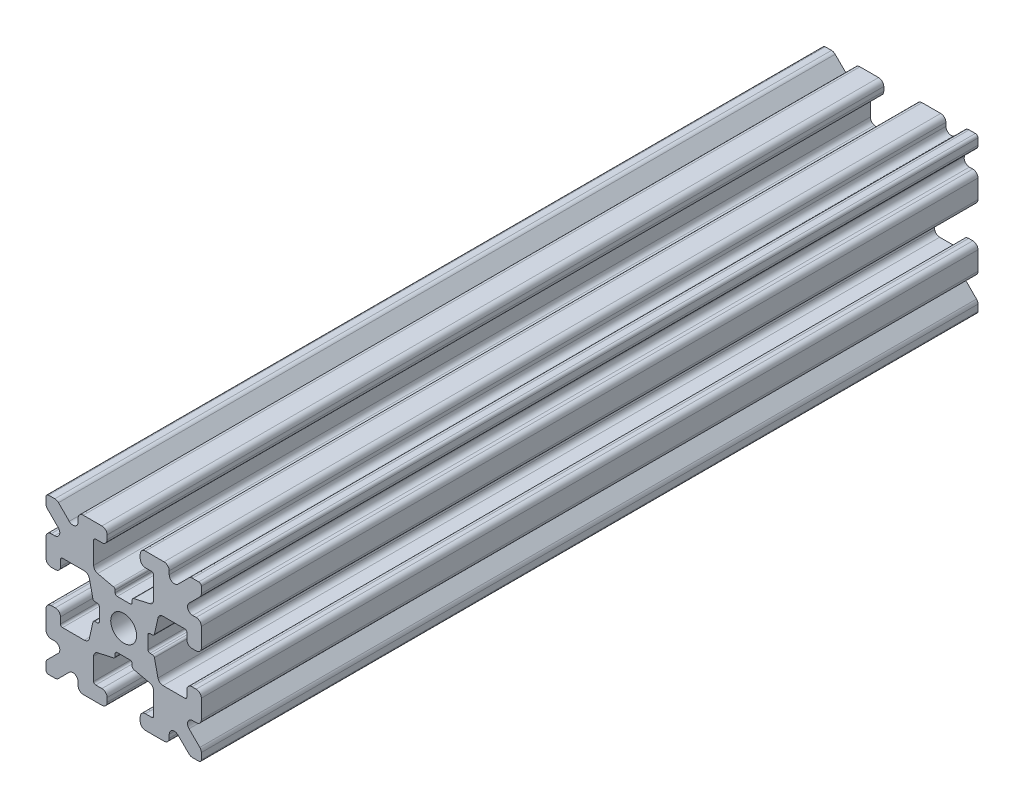
SolidWorks part; units mm, degrees
ref_plane "Front Plane" through (0, 0, 0) normal (0, 0, 1) x (1, 0, 0)
ref_plane "Top Plane" through (0, 0, 0) normal (0, 1, 0) x (1, 0, 0)
ref_plane "Right Plane" through (0, 0, 0) normal (1, 0, 0) x (0, 0, -1)
sketch "Sketch1" plane through (0, 0, 0) normal (0, 0, 1) x (1, 0, 0)
  line L1 (-7.5, -7.5) -> (7.5, -7.5)
  line L2 (-7.5, -7.5) -> (-7.5, 7.5)
  line L3 (-7.5, 7.5) -> (7.5, 7.5)
  line L4 (7.5, -7.5) -> (7.5, 7.5)
  line L5 (-7.5, -7.5) -> (7.5, 7.5) construction
  line L6 (-7.5, 7.5) -> (7.5, -7.5) construction
  circle A0 centre (0, 0) radius 1.25
  point P0 (0, 0)
  dimension "D2" = 2.5
  dimension "D1" = 15
extrude "Boss-Extrude1" add sketch "Sketch1" along normal mid plane 75
fillet "Fillet1" radius 0.25 4 edges at (7.5, -7.5, 0) (-7.5, -7.5, 0) (7.5, 7.5, 0) (-7.5, 7.5, 0)
sketch "Sketch2" plane through (0, 0, 37.5) normal (0, 0, 1) x (1, 0, 0)
  line L0 (-7.5, 7.25) -> (-7.5, -7.25) construction
  line L1 (-7.5, 1.6) -> (-6.1, 1.6)
  line L2 (-7.5, 1.6) -> (-7.5, -1.6)
  line L3 (-7.5, -1.6) -> (-6.1, -1.6)
  line L4 (-6.1, 1.6) -> (-6.1, 2.9)
  line L5 (0, 0) -> (-12.1036, 0) construction
  line L6 (-6.1, -2.9) -> (-3.4, -2.9)
  line L7 (0, 0) -> (-7.25, 7.25) construction
  line L8 (-6.1, 2.9) -> (-3.4, 2.9)
  line L9 (-3.4, -2.9) -> (-3.4, 2.9)
  line L10 (55, 0) -> (-55, 0) construction
  line L11 (-6.1, -2.9) -> (-6.1, -1.6)
  line L12 (2.9, 6.1) -> (1.6, 6.1)
  line L13 (2.9, 3.4) -> (-2.9, 3.4)
  line L14 (-2.9, 6.1) -> (-2.9, 3.4)
  line L15 (2.9, 6.1) -> (2.9, 3.4)
  line L16 (-1.6, 6.1) -> (-2.9, 6.1)
  line L17 (1.6, 7.5) -> (1.6, 6.1)
  line L18 (-1.6, 7.5) -> (1.6, 7.5)
  line L19 (-1.6, 7.5) -> (-1.6, 6.1)
  line L20 (-1.6, -7.5) -> (-1.6, -6.1)
  line L21 (-1.6, -7.5) -> (1.6, -7.5)
  line L22 (1.6, -7.5) -> (1.6, -6.1)
  line L23 (-1.6, -6.1) -> (-2.9, -6.1)
  line L24 (2.9, -6.1) -> (2.9, -3.4)
  line L25 (-2.9, -6.1) -> (-2.9, -3.4)
  line L26 (2.9, -3.4) -> (-2.9, -3.4)
  line L27 (2.9, -6.1) -> (1.6, -6.1)
  line L28 (6.1, -2.9) -> (6.1, -1.6)
  line L29 (3.4, -2.9) -> (3.4, 2.9)
  line L30 (6.1, 2.9) -> (3.4, 2.9)
  line L31 (6.1, -2.9) -> (3.4, -2.9)
  line L32 (6.1, 1.6) -> (6.1, 2.9)
  line L33 (7.5, -1.6) -> (6.1, -1.6)
  line L34 (7.5, 1.6) -> (7.5, -1.6)
  line L35 (7.5, 1.6) -> (6.1, 1.6)
  dimension "D1" = 3.2
  dimension "D2" = 5.8
  dimension "D3" = 1.4
  dimension "D4" = 2.7
extrude "Cut-Extrude1" cut sketch "Sketch2" against normal through all
sketch "Sketch4" plane through (0, 0, 37.5) normal (0, 0, 1) x (1, 0, 0)
  line L0 (-3.4, 2.9) -> (-2.75, 0)
  line L1 (55, 0) -> (-55, 0) construction
  line L2 (-2.75, 0) -> (-3.4, -2.9)
  line L3 (-3.4, -2.9) -> (-3.4, 2.9) construction
  line L4 (-3.4, 2.9) -> (-3.4, -2.9)
  line L5 (-2.9, 3.4) -> (0, 2.75)
  line L6 (0, 2.75) -> (2.9, 3.4)
  line L7 (2.9, 3.4) -> (-2.9, 3.4)
  line L8 (3.4, 2.9) -> (2.75, 0)
  line L9 (2.75, 0) -> (3.4, -2.9)
  line L10 (3.4, -2.9) -> (3.4, 2.9)
  line L11 (-2.9, -3.4) -> (0, -2.75)
  line L12 (0, -2.75) -> (2.9, -3.4)
  line L13 (2.9, -3.4) -> (-2.9, -3.4)
  circle A2 centre (0, 0) radius 2.75
  circle A3 centre (0, 0) radius 2.75 construction
  dimension "D1" = 1.5
extrude "Cut-Extrude3" cut sketch "Sketch4" against normal through all
fillet "Fillet3" radius 0.5 16 edges at (-6.1, -1.6, 0) (-7.5, -1.6, 0) (-6.1, 1.6, 0) (-7.5, 1.6, 0) (-1.6, -7.5, 0) (-1.6, -6.1, 0) (1.6, -7.5, 0) (1.6, -6.1, 0) (6.1, -1.6, 0) (7.5, -1.6, 0) (7.5, 1.6, 0) (6.1, 1.6, 0) (1.6, 7.5, 0) (1.6, 6.1, 0) (-1.6, 7.5, 0) (-1.6, 6.1, 0)
fillet "Fillet4" radius 0.5 8 edges at (-3.4, 2.9, 0) (-3.4, -2.9, 0) (2.9, -3.4, 0) (-2.9, -3.4, 0) (3.4, -2.9, 0) (3.4, 2.9, 0) (-2.9, 3.4, 0) (2.9, 3.4, 0)
fillet "Fillet5" radius 3 4 edges at (0, -2.75, 0) (2.75, 0, 0) (-2.75, 0, 0) (0, 2.75, 0)
fillet "Fillet6" radius 0.2 8 edges at (-2.9, -6.1, 0) (2.9, -6.1, 0) (6.1, -2.9, 0) (6.1, 2.9, 0) (2.9, 6.1, 0) (-2.9, 6.1, 0) (-6.1, -2.9, 0) (-6.1, 2.9, 0)
sketch "Sketch5" plane through (0, 0, 37.5) normal (0, 0, 1) x (1, 0, 0)
  line L0 (0, 0) -> (-7.25, 7.25) construction
  line L1 (-7.5, 6.4393) -> (-5.4607, 4.4)
  line L2 (-6.4393, 7.5) -> (-4.4, 5.4607)
  line L3 (-7.5, 4.4) -> (-5.4607, 4.4)
  line L4 (-3.8003, 2.9) -> (-5.9, 2.9) construction
  line L5 (0, 0) -> (-12.1819, 0) construction
  line L6 (-4.4, 7.5) -> (-4.4, 5.4607)
  line L7 (-2.9, 5.9) -> (-2.9, 3.8003) construction
  line L8 (-7.5, 6.4393) -> (-7.5, 4.4)
  line L9 (-7.5, 7.25) -> (-7.5, 2.1) construction
  line L10 (2.1, -7.5) -> (7.25, -7.5) construction
  line L11 (7.5, -7.25) -> (7.5, -2.1) construction
  line L12 (7.25, 7.5) -> (2.1, 7.5) construction
  line L13 (-2.1, 7.5) -> (-7.25, 7.5) construction
  line L14 (-4.4, 7.5) -> (-6.4393, 7.5)
  line L16 (55, 0) -> (-55, 0) construction
  line L17 (0, 0) -> (0, 10.993) construction
  line L18 (0, -54.6431) -> (0, 54.6431) construction
  line L20 (4.4, 7.5) -> (6.4393, 7.5)
  line L22 (7.5, 6.4393) -> (7.5, 4.4)
  line L23 (4.4, 7.5) -> (4.4, 5.4607)
  line L24 (7.5, 4.4) -> (5.4607, 4.4)
  line L25 (6.4393, 7.5) -> (4.4, 5.4607)
  line L26 (7.5, 6.4393) -> (5.4607, 4.4)
  line L27 (7.5, -6.4393) -> (5.4607, -4.4)
  line L28 (6.4393, -7.5) -> (4.4, -5.4607)
  line L29 (7.5, -4.4) -> (5.4607, -4.4)
  line L30 (4.4, -7.5) -> (4.4, -5.4607)
  line L31 (7.5, -6.4393) -> (7.5, -4.4)
  line L33 (4.4, -7.5) -> (6.4393, -7.5)
  line L36 (-4.4, -7.5) -> (-6.4393, -7.5)
  line L38 (-7.5, -6.4393) -> (-7.5, -4.4)
  line L39 (-4.4, -7.5) -> (-4.4, -5.4607)
  line L40 (-7.5, -4.4) -> (-5.4607, -4.4)
  line L41 (-6.4393, -7.5) -> (-4.4, -5.4607)
  line L42 (-7.5, -6.4393) -> (-5.4607, -4.4)
  dimension "D1" = 1.5
  dimension "D2" = 1.5
  dimension "D3" = 1.5
extrude "Cut-Extrude4" cut sketch "Sketch5" against normal through all
fillet "Fillet8" radius 0.5 24 edges at (-5.4607, 4.4, 0) (-7.5, 4.4, 0) (-5.4607, -4.4, 0) (-7.5, -4.4, 0) (-4.4, -7.5, 0) (-4.4, -5.4607, 0) (4.4, -7.5, 0) (4.4, -5.4607, 0) (5.4607, -4.4, 0) (7.5, -4.4, 0) (7.5, 4.4, 0) (5.4607, 4.4, 0) (4.4, 5.4607, 0) (4.4, 7.5, 0) (-4.4, 5.4607, 0) (-4.4, 7.5, 0) (-6.4393, 7.5, 0) (-7.5, 6.4393, 0) (6.4393, 7.5, 0) (7.5, 6.4393, 0) (6.4393, -7.5, 0) (7.5, -6.4393, 0) (-6.4393, -7.5, 0) (-7.5, -6.4393, 0)
sketch "Sketch6" plane through (0, 0, 37.5) normal (0, 0, 1) x (1, 0, 0)
  line L0 (0, 0) -> (0, 11.013) construction
  line L1 (0.6561, 2.8971) -> (2.1235, 2.8971) construction
  line L2 (0, -54.6431) -> (0, 54.6431) construction
  line L3 (0, 0) -> (7.25, 7.25) construction
  line L4 (7.5, 0.8255) -> (7.5, -0.8255)
  line L5 (2.3471, 0.8255) -> (7.5, 0.8255)
  line L6 (0, 0) -> (12.4016, 0) construction
  line L7 (0.8255, -7.5) -> (-0.8255, -7.5)
  line L8 (2.3471, -0.8255) -> (2.3471, 0.8255)
  line L9 (0.8255, -2.3471) -> (0.8255, -7.5)
  line L10 (7.5, -0.8255) -> (2.3471, -0.8255)
  line L11 (-7.5, -0.8255) -> (-2.3471, -0.8255)
  line L12 (-2.3471, -0.8255) -> (-2.3471, 0.8255)
  line L13 (-0.8255, -2.3471) -> (0.8255, -2.3471)
  line L14 (-0.8255, 7.5) -> (-0.8255, 2.3471)
  line L15 (-0.8255, 2.3471) -> (0.8255, 2.3471)
  line L16 (-0.8255, -7.5) -> (-0.8255, -2.3471)
  line L17 (0.8255, 2.3471) -> (0.8255, 7.5)
  line L18 (0.8255, 7.5) -> (-0.8255, 7.5)
  line L19 (3.9, 7.5) -> (2.1, 7.5) construction
  line L20 (-2.3471, 0.8255) -> (-7.5, 0.8255)
  line L21 (-7.5, 0.8255) -> (-7.5, -0.8255)
  point P5 (0, -2.5973)
  point P7 (0, 2.5973)
  dimension "D3" = 0.55
  dimension "D1" = 1.651
extrude "Cut-Extrude5" cut sketch "Sketch6" against normal through all
fillet "Fillet10" radius 0.2 16 edges at (-2.935, 0.8255, 0) (-2.935, -0.8255, 0) (2.935, -0.8255, 0) (2.935, 0.8255, 0) (0.8255, 2.935, 0) (-0.8255, 2.935, 0) (-2.3471, 0.8255, 0) (-2.3471, -0.8255, 0) (0.8255, 2.3471, 0) (-0.8255, 2.3471, 0) (2.3471, 0.8255, 0) (2.3471, -0.8255, 0) (0.8255, -2.935, 0) (0.8255, -2.3471, 0) (-0.8255, -2.3471, 0) (-0.8255, -2.935, 0)
